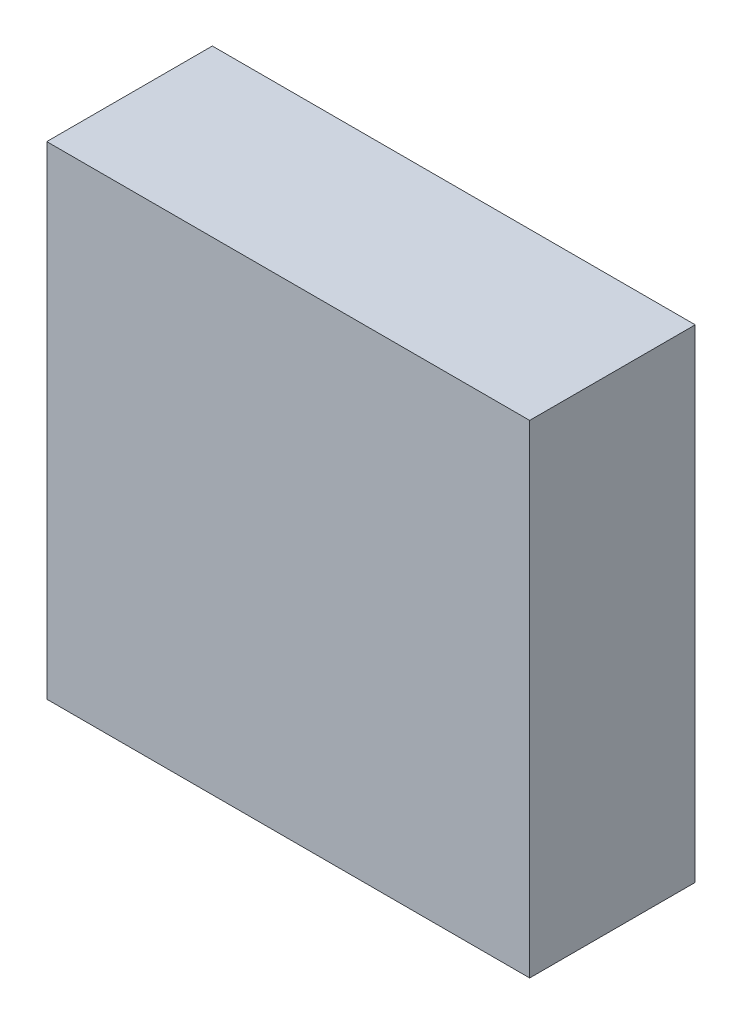
SolidWorks part; units mm, degrees
ref_plane "前视基准面" through (0, 0, 0) normal (0, 0, 1) x (1, 0, 0)
ref_plane "上视基准面" through (0, 0, 0) normal (0, 1, 0) x (1, 0, 0)
ref_plane "右视基准面" through (0, 0, 0) normal (1, 0, 0) x (0, 0, -1)
sketch "草图1" plane through (0, 0, 0) normal (0, 0, 1) x (1, 0, 0)
  line L0 (-1.75, 1.75) -> (1.75, 1.75)
  line L1 (1.75, 1.75) -> (1.75, -1.75)
  line L2 (1.75, -1.75) -> (-1.75, -1.75)
  line L3 (-1.75, -1.75) -> (-1.75, 1.75)
extrude "Component_Outline" add sketch "草图1" along normal blind 1.2 separate body
sketch3d "3D草图1"
  line L0 (0, 0, 0) -> (1, 0, 0)
  line L1 (0, 0, 0) -> (0, 1, 0)
  line L2 (0, 0, 0) -> (0, 0, 1)
  point P0 (0, 0, 0)
